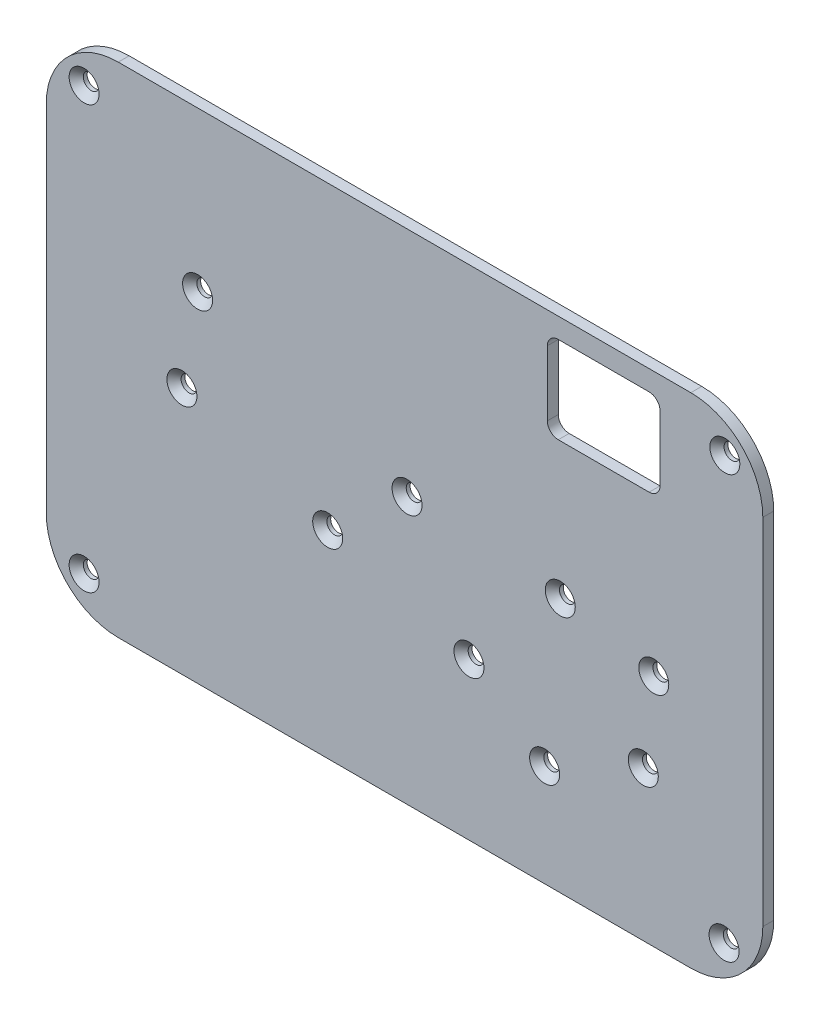
SolidWorks part; units mm, degrees
ref_plane "Спереди" through (0, 0, 0) normal (0, 0, 1) x (1, 0, 0)
ref_plane "Сверху" through (0, 0, 0) normal (0, 1, 0) x (1, 0, 0)
ref_plane "Справа" through (0, 0, 0) normal (1, 0, 0) x (0, 0, -1)
sketch "Эскиз9" plane through (0, 0, 0) normal (0, 0, 1) x (1, 0, 0)
  line L0 (89.2786, -11) -> (85.3215, -11)
  line L1 (79.0604, -10) -> (0, -10)
  line L2 (-10, 0) -> (-10, 31.7451)
  line L3 (-11, 38.0208) -> (-11, 41.9792)
  line L4 (-10, 48.1396) -> (-10, 65)
  line L5 (0, 75) -> (12.025, 75)
  line L6 (12.025, 75) -> (12.025, 78.2)
  line L7 (12.025, 78.2) -> (0, 78.2)
  line L8 (-13.2, 65) -> (-13.2, 0)
  line L9 (0, -13.2) -> (105, -13.2)
  line L10 (118.2, 0) -> (118.2, 65)
  line L11 (105, 78.2) -> (30.025, 78.2)
  line L12 (30.025, 78.2) -> (30.025, 75)
  line L13 (30.025, 75) -> (105, 75)
  line L14 (115, 65) -> (115, 0)
  line L15 (105, -10) -> (95.3396, -10)
  circle A0 centre (-6.2627, 71.3457) radius 2.75
  circle A1 centre (-6.2627, -6.1474) radius 2.75
  circle A2 centre (111.0955, -6.1474) radius 2.75
  circle A3 centre (111.2331, 71.3457) radius 2.75
  arc A4 (93.9799, -9.4667) -> (95.3396, -10) centre (95.3396, -8) ccw
  arc A5 (93.9799, -9.4667) -> (92.5665, -9.5204) centre (93.3, -10.2) ccw
  arc A6 (91.5856, -10.1011) -> (92.5665, -9.5204) centre (91.0994, -8.1611) ccw
  arc A7 (91.5856, -10.1011) -> (90.4374, -10.6301) centre (92.4155, -13.4129) ccw
  arc A8 (89.2786, -11) -> (90.4374, -10.6301) centre (89.2786, -9) ccw
  arc A9 (84.1626, -10.63) -> (85.3215, -11) centre (85.3215, -9) ccw
  arc A10 (84.1626, -10.63) -> (82.8537, -10.0647) centre (82.1842, -13.4126) ccw
  arc A11 (81.8153, -9.5012) -> (82.8537, -10.0647) centre (83.2459, -8.1035) ccw
  arc A12 (81.8153, -9.5012) -> (80.4201, -9.4667) centre (81.1, -10.2) ccw
  arc A13 (79.0604, -10) -> (80.4201, -9.4667) centre (79.0604, -8) ccw
  arc A14 (-1.5835, -9.8738) -> (0, -10) centre (0, 0) ccw
  arc A15 (-3.1229, -7.1543) -> (-1.5835, -9.8738) centre (-1.2668, -7.8991) ccw
  arc A16 (-3.1229, -7.1543) -> (-7.1543, -3.1229) centre (-6, -6) ccw
  arc A17 (-9.8738, -1.5835) -> (-7.1543, -3.1229) centre (-7.8991, -1.2668) ccw
  arc A18 (-10, 0) -> (-9.8738, -1.5835) centre (0, 0) ccw
  arc A19 (-9.5149, 33.0509) -> (-10, 31.7451) centre (-8, 31.7451) ccw
  arc A20 (-9.5149, 33.0509) -> (-9.5827, 34.8219) centre (-10.5, 33.9) ccw
  arc A21 (-10.1084, 35.7395) -> (-9.5827, 34.8219) centre (-8.172, 36.2397) ccw
  arc A22 (-10.1084, 35.7395) -> (-10.6306, 36.8627) centre (-13.4142, 34.8858) ccw
  arc A23 (-11, 38.0208) -> (-10.6306, 36.8627) centre (-9, 38.0208) ccw
  arc A24 (-10.6306, 43.1373) -> (-11, 41.9792) centre (-9, 41.9792) ccw
  arc A25 (-10.6306, 43.1373) -> (-10.0831, 44.3655) centre (-13.4142, 45.1142) ccw
  arc A26 (-9.5106, 45.3756) -> (-10.0831, 44.3655) centre (-8.1318, 43.9269) ccw
  arc A27 (-9.5106, 45.3756) -> (-9.4667, 46.7799) centre (-10.2, 46.1) ccw
  arc A28 (-10, 48.1396) -> (-9.4667, 46.7799) centre (-8, 48.1396) ccw
  arc A29 (-9.8738, 66.5835) -> (-10, 65) centre (0, 65) ccw
  arc A30 (-7.1543, 68.1229) -> (-9.8738, 66.5835) centre (-7.8991, 66.2668) ccw
  arc A31 (-7.1543, 68.1229) -> (-3.1229, 72.1543) centre (-6, 71) ccw
  arc A32 (-1.5835, 74.8738) -> (-3.1229, 72.1543) centre (-1.2668, 72.8991) ccw
  arc A33 (0, 75) -> (-1.5835, 74.8738) centre (0, 65) ccw
  arc A34 (0, 78.2) -> (-13.2, 65) centre (0, 65) ccw
  arc A35 (-13.2, 0) -> (0, -13.2) centre (0, 0) ccw
  arc A36 (105, -13.2) -> (118.2, 0) centre (105, 0) ccw
  arc A37 (118.2, 65) -> (105, 78.2) centre (105, 65) ccw
  arc A38 (106.5835, 74.8738) -> (105, 75) centre (105, 65) ccw
  arc A39 (108.1229, 72.1543) -> (106.5835, 74.8738) centre (106.2668, 72.8991) ccw
  arc A40 (108.1229, 72.1543) -> (112.1543, 68.1229) centre (111, 71) ccw
  arc A41 (114.8738, 66.5835) -> (112.1543, 68.1229) centre (112.8991, 66.2668) ccw
  arc A42 (115, 65) -> (114.8738, 66.5835) centre (105, 65) ccw
  arc A43 (114.8738, -1.5835) -> (115, 0) centre (105, 0) ccw
  arc A44 (112.1543, -3.1229) -> (114.8738, -1.5835) centre (112.8991, -1.2668) ccw
  arc A45 (112.1543, -3.1229) -> (108.1229, -7.1543) centre (111, -6) ccw
  arc A46 (106.5835, -9.8738) -> (108.1229, -7.1543) centre (106.2668, -7.8991) ccw
  arc A47 (105, -10) -> (106.5835, -9.8738) centre (105, 0) ccw
sketch "Net" plane through (0, 0, 0) normal (0, 0, 1) x (1, 0, 0)
  line L0 (24.2, 33) -> (24.2, 43.5)
  line L1 (22.2, 45.5) -> (16.7, 45.5)
  line L2 (14.7, 43.5) -> (14.7, 33)
  line L3 (16.7, 31) -> (22.2, 31)
  line L4 (49.7, 24.5) -> (49.7, 35.5)
  line L5 (47.7, 37.5) -> (43.2, 37.5)
  line L6 (41.2, 35.5) -> (41.2, 24.5)
  line L7 (43.2, 22.5) -> (47.7, 22.5)
  line L8 (76.2, 28) -> (67.2, 28)
  line L9 (65.2, 26) -> (65.2, 22)
  line L10 (67.2, 20) -> (76.2, 20)
  line L11 (78.2, 22) -> (78.2, 26)
  line L12 (86.2, 32.5) -> (96.2, 32.5)
  line L13 (98.2, 34.5) -> (98.2, 35.5)
  line L14 (96.2, 37.5) -> (86.2, 37.5)
  line L15 (84.2, 35.5) -> (84.2, 34.5)
  line L16 (78.2, -9) -> (81.2, -9)
  line L17 (78.2, 0.6303) -> (78.2, -9)
  line L18 (78.2, 16) -> (78.2, 10.096)
  line L19 (69.4574, 18) -> (76.2, 18)
  line L20 (67.4574, 14.9) -> (67.4574, 16)
  line L21 (54.8273, 16.5) -> (59.2731, 16.5)
  line L22 (38.1419, 19.7) -> (47.4957, 19.7)
  line L23 (35.0419, 23) -> (35.0419, 22.8)
  line L24 (26.2, 25) -> (33.0419, 25)
  line L25 (11.5609, 29) -> (22.2, 29)
  line L26 (8.4609, 32.5) -> (8.4609, 32.1)
  line L27 (1.4933, 34.5) -> (6.4609, 34.5)
  line L28 (-8.6, 32) -> (-2.8, 32)
  line L29 (-8.6, 34) -> (-8.6, 32)
  line L30 (-2.8, 34) -> (-8.6, 34)
  line L31 (-0.8, 44) -> (-0.8, 36)
  line L32 (-8.6, 46) -> (-2.8, 46)
  line L33 (-8.6, 48) -> (-8.6, 46)
  line L34 (-2.8, 48) -> (-8.6, 48)
  line L35 (9.432, 45.5) -> (2.4724, 45.5)
  line L36 (11.432, 49.2506) -> (11.432, 47.5)
  line L37 (22.2, 47.5) -> (19.6221, 47.5)
  line L38 (37.2, 44.5) -> (27.3962, 44.5)
  line L39 (47.7, 39.5) -> (43.1161, 39.5)
  line L40 (61.2, 34.5) -> (58.0497, 34.5)
  line L41 (75.9572, 30) -> (67.0095, 30)
  line L42 (77.9572, 33.5405) -> (77.9572, 32)
  line L43 (96.2, 39.5) -> (86.2, 39.5)
  line L44 (100.2, 32.9436) -> (100.2, 35.5)
  line L45 (98.2, 17.6226) -> (98.2, 25.0883)
  line L46 (96.2, -9) -> (96.2, 9.3668)
  line L47 (93.2, -9) -> (96.2, -9)
  line L48 (93.2, 12.5) -> (93.2, -9)
  line L49 (83.2, 14.5) -> (91.2, 14.5)
  line L50 (81.2, -9) -> (81.2, 12.5)
  line L51 (93.2, 30.5) -> (82.2, 30.5)
  line L52 (80.2, 28.5) -> (80.2, 18.5)
  line L53 (82.2, 16.5) -> (93.2, 16.5)
  line L54 (95.2, 18.5) -> (95.2, 28.5)
  line L55 (61.2, 32.5) -> (53.7, 32.5)
  line L56 (51.7, 30.5) -> (51.7, 20.5)
  line L57 (53.7, 18.5) -> (61.2, 18.5)
  line L58 (63.2, 20.5) -> (63.2, 30.5)
  line L59 (39.2, 29.5) -> (39.2, 40.5)
  line L60 (37.2, 42.5) -> (28.2, 42.5)
  line L61 (26.2, 40.5) -> (26.2, 29.5)
  line L62 (28.2, 27.5) -> (37.2, 27.5)
  line L63 (12.7, 38.5) -> (12.7, 41.5)
  line L64 (10.7, 43.5) -> (3.2, 43.5)
  line L65 (1.2, 41.5) -> (1.2, 38.5)
  line L66 (3.2, 36.5) -> (10.7, 36.5)
  circle A0 centre (14.5527, 48.9918) radius 1.45
  circle A1 centre (11.6734, 32.3071) radius 1.45
  circle A2 centre (38.4079, 23.0933) radius 1.45
  circle A3 centre (64.3154, 15.511) radius 1.45
  circle A4 centre (78.1897, 5.4989) radius 1.45
  circle A5 centre (96.2825, 14.2348) radius 1.45
  circle A6 centre (98.2, 29.7798) radius 1.45
  circle A7 centre (81.0572, 33.5405) radius 1.45
  circle A8 centre (52.9595, 35.666) radius 1.45
  arc A9 (22.2, 31) -> (24.2, 33) centre (22.2, 33) ccw
  arc A10 (24.2, 43.5) -> (22.2, 45.5) centre (22.2, 43.5) ccw
  arc A11 (16.7, 45.5) -> (14.7, 43.5) centre (16.7, 43.5) ccw
  arc A12 (14.7, 33) -> (16.7, 31) centre (16.7, 33) ccw
  arc A13 (47.7, 22.5) -> (49.7, 24.5) centre (47.7, 24.5) ccw
  arc A14 (49.7, 35.5) -> (47.7, 37.5) centre (47.7, 35.5) ccw
  arc A15 (43.2, 37.5) -> (41.2, 35.5) centre (43.2, 35.5) ccw
  arc A16 (41.2, 24.5) -> (43.2, 22.5) centre (43.2, 24.5) ccw
  arc A17 (78.2, 26) -> (76.2, 28) centre (76.2, 26) ccw
  arc A18 (67.2, 28) -> (65.2, 26) centre (67.2, 26) ccw
  arc A19 (65.2, 22) -> (67.2, 20) centre (67.2, 22) ccw
  arc A20 (76.2, 20) -> (78.2, 22) centre (76.2, 22) ccw
  arc A21 (84.2, 34.5) -> (86.2, 32.5) centre (86.2, 34.5) ccw
  arc A22 (96.2, 32.5) -> (98.2, 34.5) centre (96.2, 34.5) ccw
  arc A23 (98.2, 35.5) -> (96.2, 37.5) centre (96.2, 35.5) ccw
  arc A24 (86.2, 37.5) -> (84.2, 35.5) centre (86.2, 35.5) ccw
  arc A25 (78.2, 0.6303) -> (76.9451, 2.4863) centre (76.2, 0.6303) ccw
  arc A26 (76.9451, 8.24) -> (76.9451, 2.4863) centre (78.1, 5.3632) ccw
  arc A27 (76.9451, 8.24) -> (78.2, 10.096) centre (76.2, 10.096) ccw
  arc A28 (78.2, 16) -> (76.2, 18) centre (76.2, 16) ccw
  arc A29 (69.4574, 18) -> (67.4574, 16) centre (69.4574, 16) ccw
  arc A30 (61.2669, 14.6569) -> (67.4574, 14.9) centre (64.3574, 14.9) ccw
  arc A31 (61.2669, 14.6569) -> (59.2731, 16.5) centre (59.2731, 14.5) ccw
  arc A32 (54.8273, 16.5) -> (53.0031, 15.3198) centre (54.8273, 14.5) ccw
  arc A33 (49.3373, 16.9198) -> (53.0031, 15.3198) centre (51.1788, 16.1396) ccw
  arc A34 (49.3373, 16.9198) -> (47.4957, 19.7) centre (47.4957, 17.7) ccw
  arc A35 (35.0419, 22.8) -> (38.1419, 19.7) centre (38.1419, 22.8) ccw
  arc A36 (35.0419, 23) -> (33.0419, 25) centre (33.0419, 23) ccw
  arc A37 (24.2, 27) -> (26.2, 25) centre (26.2, 27) ccw
  arc A38 (24.2, 27) -> (22.2, 29) centre (22.2, 27) ccw
  arc A39 (8.4609, 32.1) -> (11.5609, 29) centre (11.5609, 32.1) ccw
  arc A40 (8.4609, 32.5) -> (6.4609, 34.5) centre (6.4609, 32.5) ccw
  arc A41 (1.4933, 34.5) -> (-0.2461, 33.4871) centre (1.4933, 32.5) ccw
  arc A42 (-2.8, 32) -> (-0.2461, 33.4871) centre (-2.8, 34.9366) ccw
  arc A43 (-2.8, 34) -> (-0.8, 36) centre (-2.8, 36) ccw
  arc A44 (-0.8, 44) -> (-2.8, 46) centre (-2.8, 44) ccw
  arc A45 (0.1039, 46.7509) -> (-2.8, 48) centre (-2.8, 44) ccw
  arc A46 (0.1039, 46.7509) -> (2.4724, 45.5) centre (2.4724, 48.3677) ccw
  arc A47 (9.432, 45.5) -> (11.432, 47.5) centre (9.432, 47.5) ccw
  arc A48 (17.6221, 49.4992) -> (11.432, 49.2506) centre (14.532, 49.2506) ccw
  arc A49 (17.6221, 49.4992) -> (19.6221, 47.5) centre (19.6221, 49.5) ccw
  arc A50 (25.6641, 45.5) -> (22.2, 47.5) centre (22.2, 43.5) ccw
  arc A51 (25.6641, 45.5) -> (27.3962, 44.5) centre (27.3962, 46.5) ccw
  arc A52 (41.1441, 41.1667) -> (37.2, 44.5) centre (37.2, 40.5) ccw
  arc A53 (41.1441, 41.1667) -> (43.1161, 39.5) centre (43.1161, 41.5) ccw
  arc A54 (49.9808, 38.7861) -> (47.7, 39.5) centre (47.7, 35.5) ccw
  arc A55 (49.9808, 38.7861) -> (51.8634, 38.5719) centre (51.1211, 40.4291) ccw
  arc A56 (56.0749, 36.1837) -> (51.8634, 38.5719) centre (53.0139, 35.6933) ccw
  arc A57 (56.0749, 36.1837) -> (58.0497, 34.5) centre (58.0497, 36.5) ccw
  arc A58 (65.073, 31.5) -> (61.2, 34.5) centre (61.2, 30.5) ccw
  arc A59 (65.073, 31.5) -> (67.0095, 30) centre (67.0095, 32) ccw
  arc A60 (75.9572, 30) -> (77.9572, 32) centre (75.9572, 32) ccw
  arc A61 (81.0756, 36.6404) -> (77.9572, 33.5405) centre (81.0572, 33.5405) ccw
  arc A62 (81.0756, 36.6404) -> (82.7917, 37.5936) centre (81.0875, 38.6404) ccw
  arc A63 (86.2, 39.5) -> (82.7917, 37.5936) centre (86.2, 35.5) ccw
  arc A64 (100.2, 35.5) -> (96.2, 39.5) centre (96.2, 35.5) ccw
  arc A65 (100.2, 32.9436) -> (100.6314, 31.7029) centre (102.2, 32.9436) ccw
  arc A66 (99.4157, 26.9281) -> (100.6314, 31.7029) centre (98.2, 29.7798) ccw
  arc A67 (99.4157, 26.9281) -> (98.2, 25.0883) centre (100.2, 25.0883) ccw
  arc A68 (98.2, 17.6226) -> (98.7318, 16.2645) centre (100.2, 17.6226) ccw
  arc A69 (97.5161, 11.2463) -> (98.7318, 16.2645) centre (96.4561, 14.1594) ccw
  arc A70 (97.5161, 11.2463) -> (96.2, 9.3668) centre (98.2, 9.3668) ccw
  arc A71 (93.2, 12.5) -> (91.2, 14.5) centre (91.2, 12.5) ccw
  arc A72 (83.2, 14.5) -> (81.2, 12.5) centre (83.2, 12.5) ccw
  arc A73 (95.2, 28.5) -> (93.2, 30.5) centre (93.2, 28.5) ccw
  arc A74 (82.2, 30.5) -> (80.2, 28.5) centre (82.2, 28.5) ccw
  arc A75 (80.2, 18.5) -> (82.2, 16.5) centre (82.2, 18.5) ccw
  arc A76 (93.2, 16.5) -> (95.2, 18.5) centre (93.2, 18.5) ccw
  arc A77 (63.2, 30.5) -> (61.2, 32.5) centre (61.2, 30.5) ccw
  arc A78 (53.7, 32.5) -> (51.7, 30.5) centre (53.7, 30.5) ccw
  arc A79 (51.7, 20.5) -> (53.7, 18.5) centre (53.7, 20.5) ccw
  arc A80 (61.2, 18.5) -> (63.2, 20.5) centre (61.2, 20.5) ccw
  arc A81 (37.2, 27.5) -> (39.2, 29.5) centre (37.2, 29.5) ccw
  arc A82 (39.2, 40.5) -> (37.2, 42.5) centre (37.2, 40.5) ccw
  arc A83 (28.2, 42.5) -> (26.2, 40.5) centre (28.2, 40.5) ccw
  arc A84 (26.2, 29.5) -> (28.2, 27.5) centre (28.2, 29.5) ccw
  arc A85 (10.7, 36.5) -> (12.7, 38.5) centre (10.7, 38.5) ccw
  arc A86 (12.7, 41.5) -> (10.7, 43.5) centre (10.7, 41.5) ccw
  arc A87 (3.2, 43.5) -> (1.2, 41.5) centre (3.2, 41.5) ccw
  arc A88 (1.2, 38.5) -> (3.2, 36.5) centre (3.2, 38.5) ccw
  point P0 (0, 0)
sketch "Outline" plane through (0, 0, 0) normal (0, 0, 1) x (1, 0, 0)
  line L7 (12.025, 78.2) -> (0, 78.2)
  line L8 (-13.2, 65) -> (-13.2, 0)
  line L9 (0, -13.2) -> (105, -13.2)
  line L10 (118.2, 0) -> (118.2, 65)
  line L11 (105, 78.2) -> (12.025, 78.2)
  arc A34 (0, 78.2) -> (-13.2, 65) centre (0, 65) ccw
  arc A35 (-13.2, 0) -> (0, -13.2) centre (0, 0) ccw
  arc A36 (105, -13.2) -> (118.2, 0) centre (105, 0) ccw
  arc A37 (118.2, 65) -> (105, 78.2) centre (105, 65) ccw
  point P0 (0, 0)
extrude "Бобышка-Вытянуть1" add sketch "Outline" along normal blind 2
hole_wizard "Отверстие с зазором M2.51" positions "Эскиз7" profile "Эскиз8" hole size "M2.5" standard "Ansi Metric" end condition through all
sketch "Эскиз7" plane through (0, 0, 2) normal (0, 0, 1) x (1, 0, 0)
  point P0 (14.5527, 48.9918)
  point P3 (11.6734, 32.3071)
  point P6 (38.4079, 23.0933)
  point P9 (64.3154, 15.511)
  point P12 (78.1897, 5.4989)
  point P15 (96.2825, 14.2348)
  point P18 (98.2, 29.7798)
  point P21 (81.0572, 33.5405)
  point P24 (52.9595, 35.666)
  point P27 (-6.2627, 71.3457)
  point P30 (-6.2627, -6.1474)
  point P33 (111.0955, -6.1474)
  point P36 (111.2331, 71.3457)
sketch "Эскиз8" plane through (14.5527, 48.9918, 2) normal (1, 0, 0) x (0, -1, 0)
  line L0 (0, 0) -> (0, 2)
  line L1 (0, 2) -> (1.45, 2)
  line L2 (1.45, 2) -> (1.45, 1.3)
  line L3 (1.45, 1.3) -> (2.75, 0)
  line L5 (2.75, 0) -> (0, 0)
  line L6 (-1.45, 1.3) -> (-2.75, 0) construction
  line L11 (0, -6.35) -> (0, 107.95) construction
  dimension "Диаметр сквозного отверстия" = 2.9
  dimension "Глубина сквозного отверстия" = 2
  dimension "Диаметр передней зенковки" = 5.5
  dimension "Угол передней зенковки" = 90
extrude "Вырез-Вытянуть1" cut sketch "Эскиз10" along normal through all both and the other way through all
sketch "Эскиз10" plane through (0, 0, -9.9367) normal (0, 0, 1) x (1, 0, 0)
  line L1 (80.6895, 74.5) -> (97.3467, 74.5)
  line L2 (78.6895, 72.5) -> (78.6895, 60.5727)
  line L3 (80.6895, 58.5727) -> (97.3467, 58.5727)
  line L4 (99.3467, 72.5) -> (99.3467, 60.5727)
  arc A0 (78.6895, 60.5727) -> (80.6895, 58.5727) centre (80.6895, 60.5727) ccw
  arc A1 (97.3467, 58.5727) -> (99.3467, 60.5727) centre (97.3467, 60.5727) ccw
  arc A2 (97.3467, 74.5) -> (99.3467, 72.5) centre (97.3467, 72.5) cw
  arc A3 (80.6895, 74.5) -> (78.6895, 72.5) centre (80.6895, 72.5) ccw
  point P14 (78.6895, 74.5)
